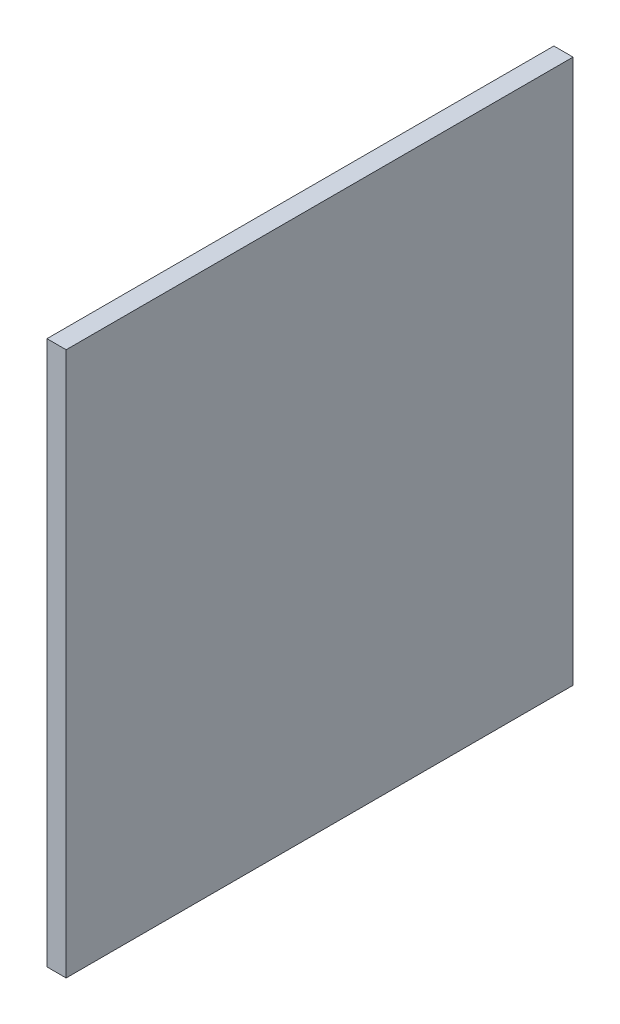
SolidWorks part; units mm, degrees
ref_plane "Front Plane" through (0, 0, 0) normal (0, 0, 1) x (1, 0, 0)
ref_plane "Top Plane" through (0, 0, 0) normal (0, 1, 0) x (1, 0, 0)
ref_plane "Right Plane" through (0, 0, 0) normal (1, 0, 0) x (0, 0, -1)
sketch "Sketch1" plane through (0, 0, 0) normal (1, 0, 0) x (0, 0, -1)
  line L1 (83.85, -90) -> (-83.85, -90)
  line L2 (83.85, -90) -> (83.85, 90)
  line L3 (83.85, 90) -> (-83.85, 90)
  line L4 (-83.85, -90) -> (-83.85, 90)
  line L5 (83.85, -90) -> (-83.85, 90) construction
  line L6 (83.85, 90) -> (-83.85, -90) construction
  point P0 (0, 0)
  dimension "D1" = 167.7
  dimension "D2" = 180
extrude "Boss-Extrude1" add sketch "Sketch1" along normal blind 6.35
